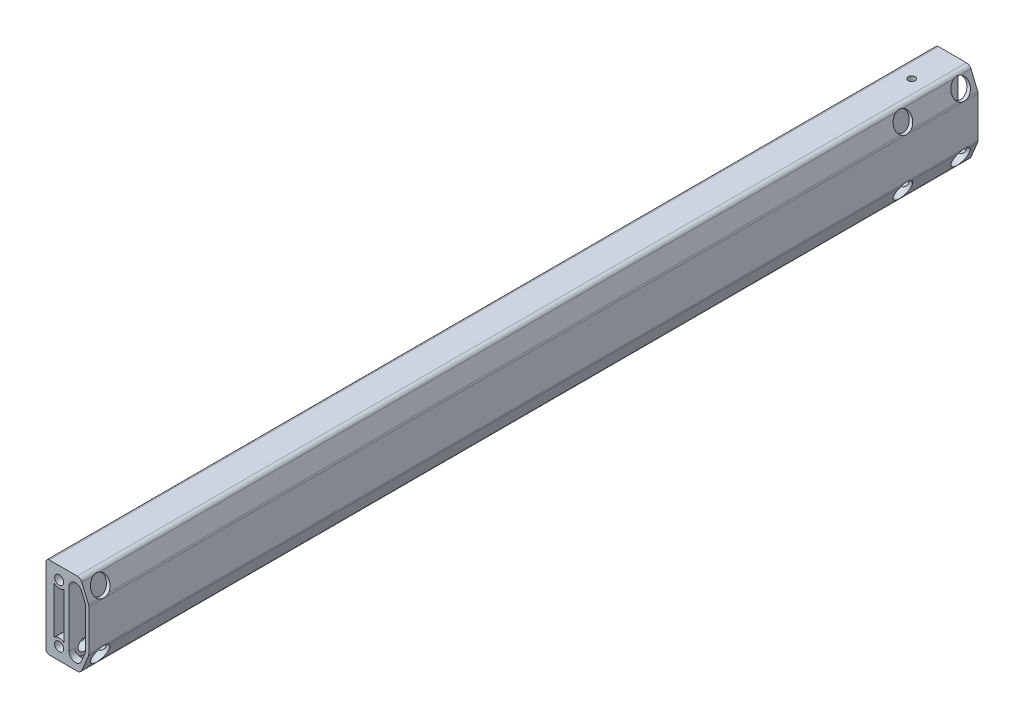
SolidWorks part; units mm, degrees
ref_plane "前视基准面" through (0, 0, 0) normal (0, 0, 1) x (1, 0, 0)
ref_plane "上视基准面" through (0, 0, 0) normal (0, 1, 0) x (1, 0, 0)
ref_plane "右视基准面" through (0, 0, 0) normal (1, 0, 0) x (0, 0, -1)
sketch "草图1" plane through (0, 0, 0) normal (0, 0, 1) x (1, 0, 0)
  line L127 (1267.4411, 1153.2807) -> (1313.3964, 1153.2807) construction
  line L129 (1284.9549, 1167.4266) -> (1284.9549, 1139.1348)
  line L130 (1279.9549, 1143.2807) -> (1279.9549, 1130.2807)
  line L134 (1279.9549, 1176.2807) -> (1279.9549, 1163.2807)
  line L135 (1298.9549, 1128.2807) -> (1281.9549, 1128.2807)
  line L136 (1281.9549, 1178.2807) -> (1298.9549, 1178.2807)
  line L137 (1290.9549, 1167.4266) -> (1290.9549, 1139.1348)
  line L138 (1293.9549, 1170.3807) -> (1293.9549, 1136.1807)
  line L139 (1305.9549, 1140.8807) -> (1305.9549, 1165.6807)
  line L140 (1303.9549, 1140.8807) -> (1303.9549, 1165.6807)
  line L141 (1305.7241, 1166.8346) -> (1301.7241, 1176.4346)
  line L142 (1303.8779, 1166.0653) -> (1301.4549, 1171.8807)
  line L143 (1305.7241, 1139.7269) -> (1301.7241, 1130.1269)
  line L144 (1303.8779, 1140.4961) -> (1301.4549, 1134.6807)
  line L145 (1279.9549, 1163.2807) -> (1279.9549, 1143.2807)
  arc A25 (1301.7241, 1176.4346) -> (1298.9549, 1178.2807) centre (1298.9549, 1175.2807) ccw
  arc A26 (1281.9549, 1178.2807) -> (1279.9549, 1176.2807) centre (1281.9549, 1176.2807) ccw
  arc A27 (1279.9549, 1130.2807) -> (1281.9549, 1128.2807) centre (1281.9549, 1130.2807) ccw
  arc A28 (1305.9549, 1165.6807) -> (1305.7241, 1166.8346) centre (1302.9549, 1165.6807) ccw
  arc A29 (1303.9549, 1165.6807) -> (1303.8779, 1166.0653) centre (1302.9549, 1165.6807) ccw
  arc A30 (1305.7241, 1139.7269) -> (1305.9549, 1140.8807) centre (1302.9549, 1140.8807) ccw
  arc A31 (1303.8779, 1140.4961) -> (1303.9549, 1140.8807) centre (1302.9549, 1140.8807) ccw
  arc A32 (1298.9549, 1128.2807) -> (1301.7241, 1130.1269) centre (1298.9549, 1131.2807) ccw
  arc A33 (1301.4549, 1171.8807) -> (1293.9549, 1170.3807) centre (1297.8549, 1170.3807) ccw
  arc A34 (1293.9549, 1136.1807) -> (1301.4549, 1134.6807) centre (1297.8549, 1136.1807) ccw
  circle A35 centre (1287.9549, 1135.7807) radius 2.75
  circle A36 centre (1287.9549, 1170.7807) radius 2.75
  arc A37 (1290.9549, 1139.1348) -> (1284.9549, 1139.1348) centre (1287.9549, 1135.7807) ccw
  arc A38 (1284.9549, 1167.4266) -> (1290.9549, 1167.4266) centre (1287.9549, 1170.7807) ccw
extrude "拉伸1" add sketch "草图1" against normal blind 540
sketch "草图2" plane through (1279.9549, 0, 0) normal (-1, 0, 0) x (0, 0, 1)
  line L0 (-540, 1153.2807) -> (0, 1153.2807) construction
  line L1 (-540, 1176.2807) -> (-540, 1130.2807) construction
  line L2 (0, 1176.2807) -> (0, 1130.2807) construction
  line L3 (-540, 1163.2807) -> (-485, 1163.2807)
  line L5 (-485, 1143.2807) -> (-540, 1143.2807)
  line L6 (-540, 1143.2807) -> (-540, 1163.2807)
  arc A0 (-485, 1143.2807) -> (-485, 1163.2807) centre (-485, 1153.2807) ccw
  dimension "D1" = 55
  dimension "D2" = 10
  dimension "D3" = 20
extrude "拉伸2" cut sketch "草图2" against normal blind 2.5
sketch "草图3" plane through (1305.9549, 0, 0) normal (1, 0, 0) x (0, 0, -1)
  line L0 (540, 1153.2807) -> (0, 1153.2807) construction
  line L1 (540, 1140.8807) -> (540, 1165.6807) construction
  line L2 (0, 1140.8807) -> (0, 1165.6807) construction
  line L3 (540, 1166.8346) -> (540, 1176.4346) construction
  circle A0 centre (531.5, 1171.2807) radius 3.5
  circle A1 centre (496.5, 1171.2807) radius 3.5
  circle A2 centre (531.5, 1135.2807) radius 3.5
  circle A3 centre (496.5, 1135.2807) radius 3.5
  circle A4 centre (9, 1171.2807) radius 3.5
  circle A5 centre (9, 1135.2807) radius 3.5
  dimension "D1" = 7
  dimension "D2" = 7
  dimension "D3" = 7
  dimension "D4" = 7
  dimension "D5" = 7
  dimension "D6" = 7
  dimension "D8" = 18
  dimension "D9" = 9
  dimension "D16" = 35
  dimension "D17" = 35
  dimension "D7" = 36
  dimension "D10" = 36
  dimension "D11" = 36
  dimension "D12" = 18
  dimension "D13" = 18
  dimension "D14" = 8.5
  dimension "D15" = 8.5
extrude "拉伸3" cut sketch "草图3" against normal through all
sketch "草图4" plane through (1305.9549, 0, 0) normal (1, 0, 0) x (0, 0, -1)
  circle A0 centre (496.5, 1171.2807) radius 5.5
  circle A1 centre (531.5, 1171.2807) radius 5.5
  circle A2 centre (496.5, 1135.2807) radius 5.5
  circle A3 centre (531.5, 1135.2807) radius 5.5
  circle A4 centre (9, 1171.2807) radius 5.5
  circle A5 centre (9, 1135.2807) radius 5.5
  dimension "D1" = 11
  dimension "D2" = 11
  dimension "D3" = 11
  dimension "D4" = 11
  dimension "D5" = 11
  dimension "D6" = 11
extrude "拉伸4" cut sketch "草图4" against normal blind 12
hole_wizard "M5 螺纹孔1" positions "草图7" profile "草图6" tap size "M5" standard "ISO"
sketch "草图7" plane through (0, 1178.2807, 0) normal (0, 1, 0) x (-1, 0, 0)
  point P1 (-1290.7049, -515)
sketch "草图6" plane through (1290.7049, 1178.2807, -515) normal (1, 0, 0) x (0, 0, 1)
  line L0 (0, 0) -> (0, 13.6618)
  line L1 (0, 13.6618) -> (2.1, 12.4)
  line L2 (2.1, 12.4) -> (2.1, 0)
  line L5 (2.1, 0) -> (0, 0)
  line L10 (0, 13.6618) -> (-2.1, 12.4) construction
  line L11 (0, -6.35) -> (0, 107.95) construction
  dimension "螺纹孔钻头直径" = 4.2
  dimension "螺纹孔钻头深度" = 12.4
  dimension "导头角度" = 118
cosmetic thread "孔螺蚊线1" parameters "D1"=10, "D2"=5
hole_wizard "M5 螺纹孔2" positions "草图9" profile "草图8" tap size "M5" standard "ISO"
sketch "草图9" plane through (0, 1128.2807, 0) normal (0, -1, 0) x (1, 0, 0)
  point P1 (1290.7049, -515)
sketch "草图8" plane through (1290.7049, 1128.2807, -515) normal (1, 0, 0) x (0, 0, -1)
  line L0 (0, 0) -> (0, 13.6618)
  line L1 (0, 13.6618) -> (2.1, 12.4)
  line L2 (2.1, 12.4) -> (2.1, 0)
  line L5 (2.1, 0) -> (0, 0)
  line L10 (0, 13.6618) -> (-2.1, 12.4) construction
  line L11 (0, -6.35) -> (0, 107.95) construction
  dimension "螺纹孔钻头直径" = 4.2
  dimension "螺纹孔钻头深度" = 12.4
  dimension "导头角度" = 118
cosmetic thread "孔螺蚊线2" parameters "D1"=10, "D2"=5
